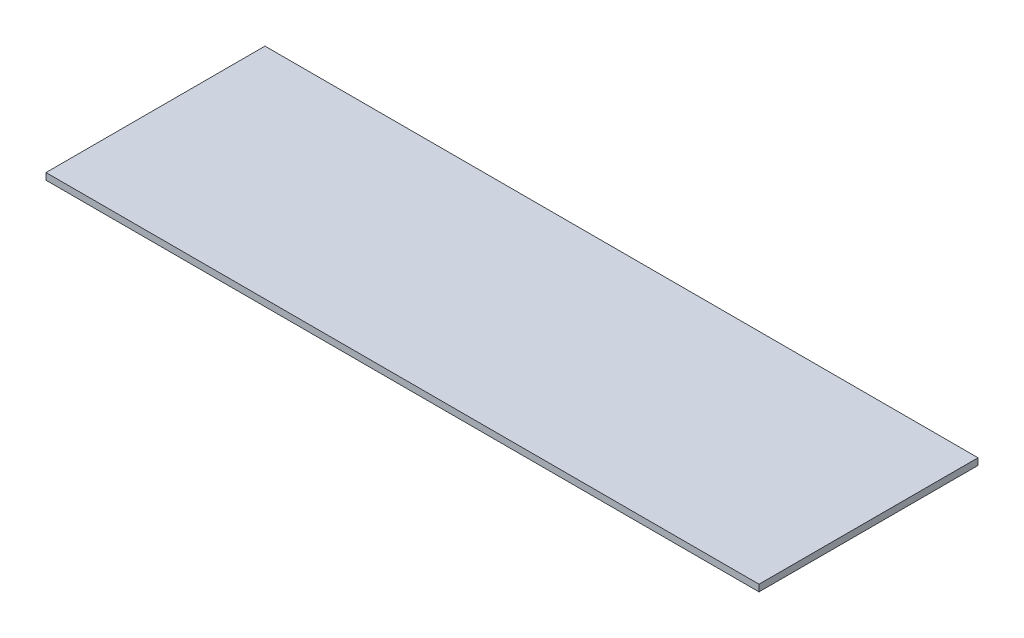
SolidWorks part; units mm, degrees
ref_plane "前视基准面" through (0, 0, 0) normal (0, 0, 1) x (1, 0, 0)
ref_plane "上视基准面" through (0, 0, 0) normal (0, 1, 0) x (1, 0, 0)
ref_plane "右视基准面" through (0, 0, 0) normal (1, 0, 0) x (0, 0, -1)
sketch "草图1" plane through (0, 0, 0) normal (0, 1, 0) x (1, 0, 0)
  line L1 (-160, 49.14) -> (160, 49.14)
  line L2 (-160, 49.14) -> (-160, -49.14)
  line L3 (-160, -49.14) -> (160, -49.14)
  line L4 (160, 49.14) -> (160, -49.14)
  line L5 (-160, 49.14) -> (160, -49.14) construction
  line L6 (-160, -49.14) -> (160, 49.14) construction
  point P0 (0, 0)
  dimension "D1" = 320
  dimension "D2" = 98.28
extrude "凸台-拉伸1" add sketch "草图1" along normal blind 3
